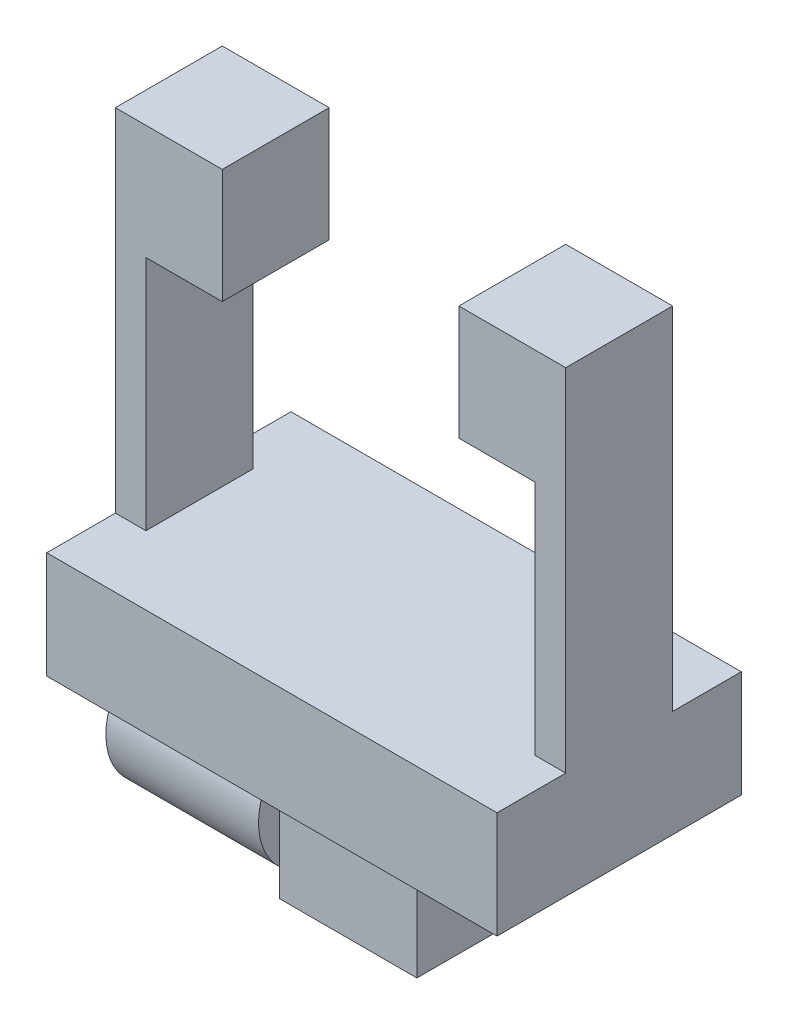
SolidWorks part; units mm, degrees
material "6061-T6 (SS)"
ref_plane "Front Plane" through (0, 0, 0) normal (0, 0, 1) x (1, 0, 0)
ref_plane "Top Plane" through (0, 0, 0) normal (0, 1, 0) x (1, 0, 0)
ref_plane "Right Plane" through (0, 0, 0) normal (1, 0, 0) x (0, 0, -1)
sketch "Sketch1" plane through (0, 0, 0) normal (0, 0, 1) x (1, 0, 0)
  line L1 (-37.465, -8.89) -> (37.465, -8.89)
  line L2 (-37.465, -8.89) -> (-37.465, 8.89)
  line L3 (-37.465, 8.89) -> (37.465, 8.89)
  line L4 (37.465, -8.89) -> (37.465, 8.89)
  line L5 (-37.465, -8.89) -> (37.465, 8.89) construction
  line L6 (-37.465, 8.89) -> (37.465, -8.89) construction
  point P0 (0, 0)
  dimension "D1" = 74.93
  dimension "D2" = 17.78
extrude "Boss-Extrude1" add sketch "Sketch1" along normal mid plane 40.64
sketch "Sketch2" plane through (0, 0, 0) normal (0, 0, 1) x (1, 0, 0)
  line L1 (-37.465, 8.89) -> (-32.385, 8.89)
  line L2 (-37.465, 8.89) -> (-37.465, 48.26)
  line L3 (-37.465, 48.26) -> (-32.385, 48.26)
  line L4 (-32.385, 8.89) -> (-32.385, 48.26)
  line L5 (37.465, 8.89) -> (32.385, 8.89)
  line L6 (37.465, 8.89) -> (37.465, 48.26)
  line L7 (37.465, 48.26) -> (32.385, 48.26)
  line L8 (32.385, 8.89) -> (32.385, 48.26)
  dimension "D1" = 5.08
  dimension "D2" = 39.37
  dimension "D3" = 5.08
  dimension "D4" = 39.37
extrude "Boss-Extrude2" add sketch "Sketch2" along normal mid plane 17.78
sketch "Sketch3" plane through (0, 0, 0) normal (0, 0, 1) x (1, 0, 0)
  line L1 (37.465, 48.26) -> (19.685, 48.26)
  line L2 (37.465, 48.26) -> (37.465, 67.31)
  line L3 (37.465, 67.31) -> (19.685, 67.31)
  line L4 (19.685, 48.26) -> (19.685, 67.31)
  line L5 (-37.465, 48.26) -> (-19.685, 48.26)
  line L6 (-37.465, 48.26) -> (-37.465, 67.31)
  line L7 (-37.465, 67.31) -> (-19.685, 67.31)
  line L8 (-19.685, 48.26) -> (-19.685, 67.31)
  dimension "D1" = 17.78
  dimension "D2" = 19.05
  dimension "D3" = 17.78
  dimension "D4" = 19.05
extrude "Boss-Extrude3" add sketch "Sketch3" along normal mid plane 17.78
sketch "Sketch5" plane through (0, 0, 0) normal (0, 0, 1) x (1, 0, 0)
  line L0 (-37.465, -8.89) -> (37.465, -8.89) construction
  line L1 (-11.43, -8.89) -> (11.43, -8.89)
  line L2 (-11.43, -8.89) -> (-11.43, -34.29)
  line L3 (-11.43, -34.29) -> (11.43, -34.29)
  line L4 (11.43, -8.89) -> (11.43, -34.29)
  point P4 (0, -8.89)
  dimension "D1" = 22.86
  dimension "D2" = 25.4
extrude "Boss-Extrude4" add sketch "Sketch5" along normal mid plane 15.24
sketch "Sketch6" plane through (-11.43, 0, 0) normal (-1, 0, 0) x (0, 0, 1)
  line L0 (-7.62, -8.89) -> (7.62, -34.29) construction
  circle A0 centre (0, -21.59) radius 11.1125
  dimension "D1" = 22.225
extrude "Boss-Extrude5" add sketch "Sketch6" along normal blind 25.4
equation "\"Base Length\"= 2.95in"
equation "\"Base Height\"= 0.7in"
equation "\"Support Width\"= 0.2in"
equation "\"Support Height\"= 1.55in"
equation "\"Lip Width\"= 0.7in"
equation "\"Lip Height\"= 0.75in"
equation "\"Stem Height\"= 1in"
equation "\"Stem Width\"= 0.9in"
equation "\"Bar Diameter\"= \"Min Bar Diameter\" + \"Diameter Allow\""
equation "\"D1@Sketch1\"=\"Base Length\""
equation "\"D2@Sketch1\"=\"Base Height\""
equation "\"D1@Sketch2\"=\"Support Width\""
equation "\"D3@Sketch2\"=\"Support Width\""
equation "\"D2@Sketch2\"=\"Support Height\""
equation "\"D4@Sketch2\"=\"Support Height\""
equation "\"D3@Sketch3\"=\"Lip Width\""
equation "\"D1@Sketch3\"=\"Lip Width\""
equation "\"D4@Sketch3\"=\"Lip Height\""
equation "\"D2@Sketch3\"=\"Lip Height\""
equation "\"D1@Sketch5\"=\"Stem Width\""
equation "\"D2@Sketch5\"=\"Stem Height\""
equation "\"D1@Sketch6\"=\"Bar Diameter\""
equation "\"Base Depth\"= 1.6in"
equation "\"D1@Boss-Extrude1\"=\"Base Depth\""
equation "\"Support Depth\"= 0.7in"
equation "\"D1@Boss-Extrude2\"=\"Support Depth\""
equation "\"Lip Depth\"= 0.7in"
equation "\"D1@Boss-Extrude3\"=\"Lip Depth\""
equation "\"Stem Depth\"= 0.6in"
equation "\"D1@Boss-Extrude4\"=\"Stem Depth\""
equation "\"Bar Length\"= 1in"
equation "\"D1@Boss-Extrude5\"=\"Bar Length\""
equation "\"Bar Moment\"= 600"
equation "\"Stress Allow\"= 10000"
equation "\"Min Bar Diameter\"= ( 32 * \"Bar Moment\" / ( 3.14 * \"Stress Allow\" ) ) ^ ( 1 / 3 ) * ( 1in )"
equation "\"Diameter Allow\"= 0.875in - ( 32 * 600 / ( 3.14 * 10000 ) ) ^ ( 1 / 3 ) * 1in"
